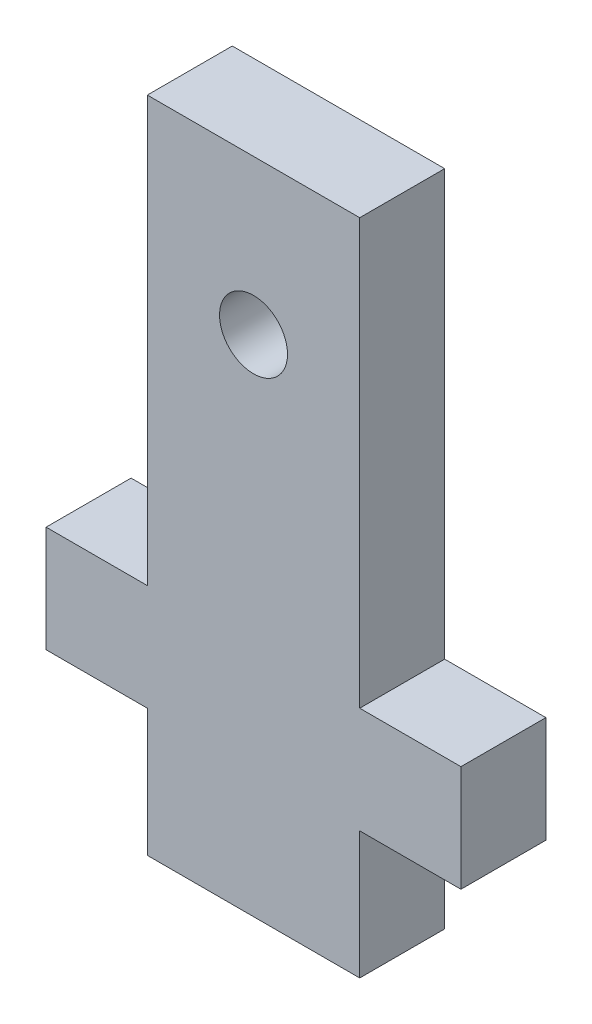
SolidWorks part; units mm, degrees
ref_plane "Front Plane" through (0, 0, 0) normal (0, 0, 1) x (1, 0, 0)
ref_plane "Top Plane" through (0, 0, 0) normal (0, 1, 0) x (1, 0, 0)
ref_plane "Right Plane" through (0, 0, 0) normal (1, 0, 0) x (0, 0, -1)
sketch "Sketch1" plane through (0, 0, 0) normal (0, 0, 1) x (1, 0, 0)
  line L0 (0, 0) -> (12.7, 0)
  line L1 (12.7, 0) -> (12.7, 7.62)
  line L2 (12.7, 7.62) -> (18.7514, 7.62)
  line L3 (18.7514, 7.62) -> (18.7514, 13.97)
  line L4 (18.7514, 13.97) -> (12.7, 13.97)
  line L5 (12.7, 13.97) -> (12.7, 39.37)
  line L6 (12.7, 39.37) -> (0, 39.37)
  line L7 (0, 39.37) -> (0, 13.97)
  line L8 (0, 13.97) -> (-6.0514, 13.97)
  line L9 (-6.0514, 13.97) -> (-6.0514, 7.62)
  line L10 (-6.0514, 7.62) -> (0, 7.62)
  line L11 (0, 7.62) -> (0, 0)
  dimension "D1" = 6.35
  dimension "D2" = 7.62
  dimension "D3" = 25.4
  dimension "D4" = 12.7
extrude "Boss-Extrude1" add sketch "Sketch1" along normal blind 5.08
sketch "Sketch2" plane through (0, 0, 5.08) normal (0, 0, 1) x (1, 0, 0)
  line L0 (6.35, 39.37) -> (6.35, 30.1409) construction
  line L1 (12.7, 39.37) -> (0, 39.37) construction
  circle A0 centre (6.35, 30.1409) radius 2.032
  dimension "D1" = 4.064
extrude "Cut-Extrude1" cut sketch "Sketch2" against normal blind 7.62
equation "\"Foamcore\" = .1in"
equation "\"MDF\" = .2in"
equation "\"Gmaterial\"= \"MDF\""
equation "\"PVC-ID\" = \"1.590in\""
equation "\"PVC-OD\" = \"1.900in\""
equation "\"PVC-Sleeve-Width\" = \".51in\""
equation "\"D1@Boss-Extrude1\"=\"Gmaterial\""
